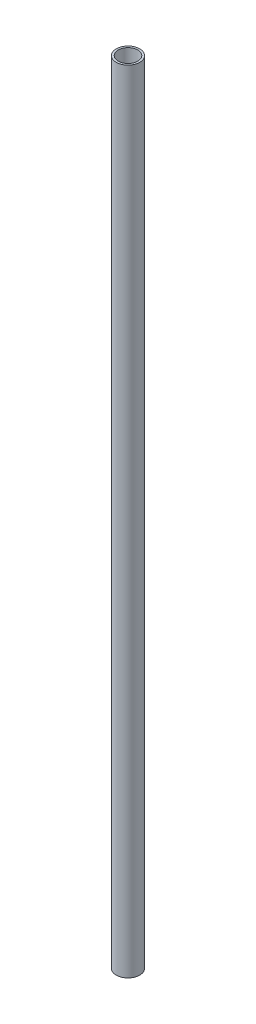
SolidWorks part; units mm, degrees
ref_plane "Front Plane" through (0, 0, 0) normal (0, 0, 1) x (1, 0, 0)
ref_plane "Top Plane" through (0, 0, 0) normal (0, 1, 0) x (1, 0, 0)
ref_plane "Right Plane" through (0, 0, 0) normal (1, 0, 0) x (0, 0, -1)
sketch "Sketch1" plane through (0, 0, 0) normal (0, 1, 0) x (1, 0, 0)
  circle A0 centre (0, 0) radius 12
  circle A1 centre (0, 0) radius 10
  dimension "D1" = 24
  dimension "D2" = 20
extrude "Boss-Extrude1" add sketch "Sketch1" along normal blind 810
